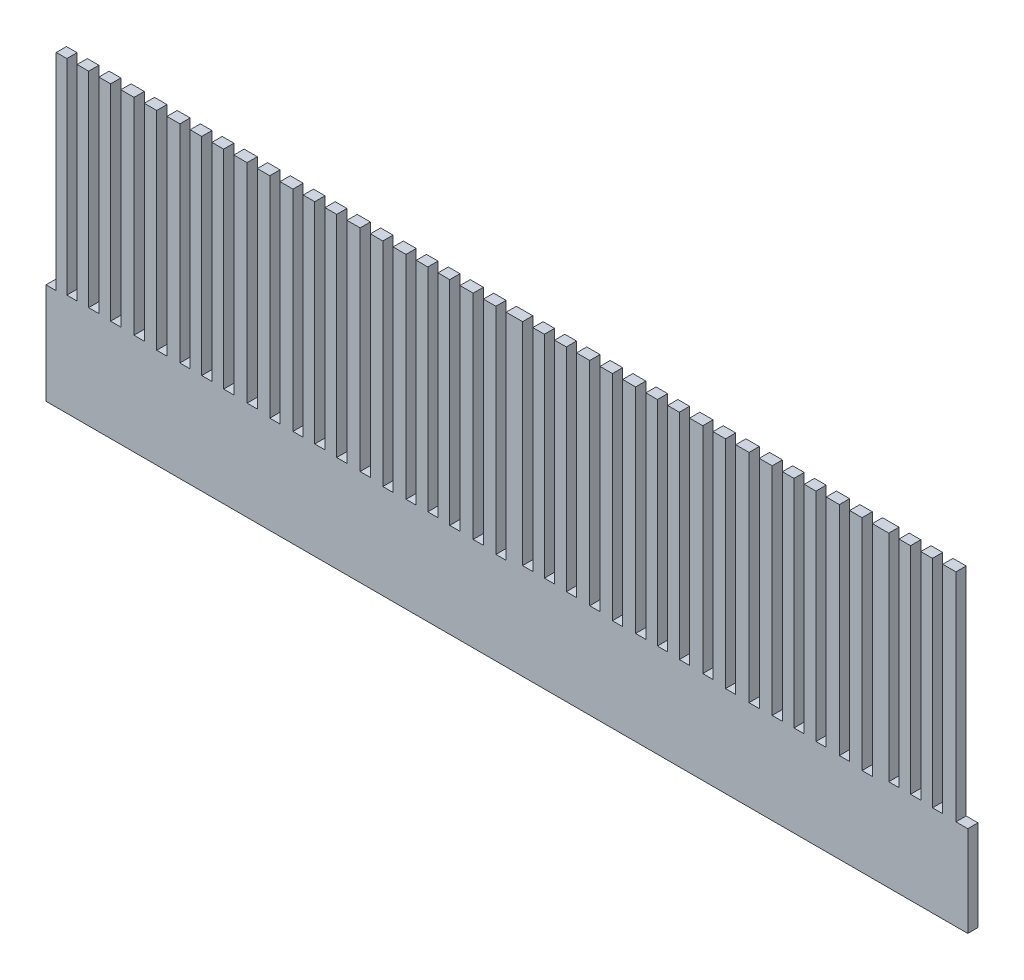
SolidWorks part; units mm, degrees
ref_plane "Front Plane" through (0, 0, 0) normal (0, 0, 1) x (1, 0, 0)
ref_plane "Top Plane" through (0, 0, 0) normal (0, 1, 0) x (1, 0, 0)
ref_plane "Right Plane" through (0, 0, 0) normal (1, 0, 0) x (0, 0, -1)
sketch "Sketch1" plane through (0, 0, 0) normal (0, 0, 1) x (1, 0, 0)
  line L1 (-53.9193, 0) -> (-8.9193, 0)
  line L2 (-53.9193, 0) -> (-53.9193, 15)
  line L3 (-53.9193, 15) -> (-8.9193, 15)
  line L4 (-8.9193, 0) -> (-8.9193, 15)
extrude "Boss-Extrude1" add sketch "Sketch1" along normal blind 0.5
sketch "Sketch2" plane through (0, 0, 0.5) normal (0, 0, 1) x (1, 0, 0)
  line L0 (-52.9014, 16.9986) -> (-52.4014, 16.9986)
  line L1 (-53.9193, 15) -> (-53.4193, 15)
  line L2 (-53.9193, 15) -> (-53.9193, 4.9255)
  line L3 (-53.9193, 4.9255) -> (-53.4193, 4.9255)
  line L4 (-53.4193, 15) -> (-53.4193, 4.9255)
  line L5 (-52.9014, 16.9986) -> (-52.9014, 4.9986)
  line L6 (-52.9014, 4.9986) -> (-52.4014, 4.9986)
  line L7 (-52.4014, 16.9986) -> (-52.4014, 4.9986)
  line L8 (-51.8373, 17.0003) -> (-51.3373, 17.0003)
  line L9 (-51.8373, 17.0003) -> (-51.8373, 5.0003)
  line L10 (-51.8373, 5.0003) -> (-51.3373, 5.0003)
  line L11 (-51.3373, 17.0003) -> (-51.3373, 5.0003)
  line L12 (-50.766, 16.9637) -> (-50.266, 16.9637)
  line L13 (-50.766, 16.9637) -> (-50.766, 4.9637)
  line L14 (-50.766, 4.9637) -> (-50.266, 4.9637)
  line L15 (-50.266, 16.9637) -> (-50.266, 4.9637)
  line L16 (-49.6216, 16.9419) -> (-49.1216, 16.9419)
  line L17 (-49.6216, 16.9419) -> (-49.6216, 4.9419)
  line L18 (-49.6216, 4.9419) -> (-49.1216, 4.9419)
  line L19 (-49.1216, 16.9419) -> (-49.1216, 4.9419)
  line L20 (-48.5139, 16.8613) -> (-48.0139, 16.8613)
  line L21 (-48.5139, 16.8613) -> (-48.5139, 4.8613)
  line L22 (-48.5139, 4.8613) -> (-48.0139, 4.8613)
  line L23 (-48.0139, 16.8613) -> (-48.0139, 4.8613)
  line L24 (-47.3825, 16.888) -> (-46.8825, 16.888)
  line L25 (-47.3825, 16.888) -> (-47.3825, 4.888)
  line L26 (-47.3825, 4.888) -> (-46.8825, 4.888)
  line L27 (-46.8825, 16.888) -> (-46.8825, 4.888)
  line L28 (-46.3184, 16.8897) -> (-45.8184, 16.8897)
  line L29 (-46.3184, 16.8897) -> (-46.3184, 4.8897)
  line L30 (-46.3184, 4.8897) -> (-45.8184, 4.8897)
  line L31 (-45.8184, 16.8897) -> (-45.8184, 4.8897)
  line L32 (-45.2472, 16.8531) -> (-44.7472, 16.8531)
  line L33 (-45.2472, 16.8531) -> (-45.2472, 4.8531)
  line L34 (-45.2472, 4.8531) -> (-44.7472, 4.8531)
  line L35 (-44.7472, 16.8531) -> (-44.7472, 4.8531)
  line L36 (-44.1027, 16.8313) -> (-43.6027, 16.8313)
  line L37 (-44.1027, 16.8313) -> (-44.1027, 4.8313)
  line L38 (-44.1027, 4.8313) -> (-43.6027, 4.8313)
  line L39 (-43.6027, 16.8313) -> (-43.6027, 4.8313)
  line L40 (-42.995, 16.7507) -> (-42.495, 16.7507)
  line L41 (-42.995, 16.7507) -> (-42.995, 4.7507)
  line L42 (-42.995, 4.7507) -> (-42.495, 4.7507)
  line L43 (-42.495, 16.7507) -> (-42.495, 4.7507)
  line L44 (-41.863, 16.7552) -> (-41.363, 16.7552)
  line L45 (-41.863, 16.7552) -> (-41.863, 4.7552)
  line L46 (-41.863, 4.7552) -> (-41.363, 4.7552)
  line L47 (-41.363, 16.7552) -> (-41.363, 4.7552)
  line L48 (-40.799, 16.7569) -> (-40.299, 16.7569)
  line L49 (-40.799, 16.7569) -> (-40.799, 4.7569)
  line L50 (-40.799, 4.7569) -> (-40.299, 4.7569)
  line L51 (-40.299, 16.7569) -> (-40.299, 4.7569)
  line L52 (-39.7277, 16.7203) -> (-39.2277, 16.7203)
  line L53 (-39.7277, 16.7203) -> (-39.7277, 4.7203)
  line L54 (-39.7277, 4.7203) -> (-39.2277, 4.7203)
  line L55 (-39.2277, 16.7203) -> (-39.2277, 4.7203)
  line L56 (-38.5832, 16.6985) -> (-38.0832, 16.6985)
  line L57 (-38.5832, 16.6985) -> (-38.5832, 4.6985)
  line L58 (-38.5832, 4.6985) -> (-38.0832, 4.6985)
  line L59 (-38.0832, 16.6985) -> (-38.0832, 4.6985)
  line L60 (-37.4756, 16.6179) -> (-36.9756, 16.6179)
  line L61 (-37.4756, 16.6179) -> (-37.4756, 4.6179)
  line L62 (-37.4756, 4.6179) -> (-36.9756, 4.6179)
  line L63 (-36.9756, 16.6179) -> (-36.9756, 4.6179)
  line L64 (-36.3442, 16.6446) -> (-35.8442, 16.6446)
  line L65 (-36.3442, 16.6446) -> (-36.3442, 4.6446)
  line L66 (-36.3442, 4.6446) -> (-35.8442, 4.6446)
  line L67 (-35.8442, 16.6446) -> (-35.8442, 4.6446)
  line L68 (-35.2801, 16.6463) -> (-34.7801, 16.6463)
  line L69 (-35.2801, 16.6463) -> (-35.2801, 4.6463)
  line L70 (-35.2801, 4.6463) -> (-34.7801, 4.6463)
  line L71 (-34.7801, 16.6463) -> (-34.7801, 4.6463)
  line L72 (-34.2088, 16.6097) -> (-33.7088, 16.6097)
  line L73 (-34.2088, 16.6097) -> (-34.2088, 4.6097)
  line L74 (-34.2088, 4.6097) -> (-33.7088, 4.6097)
  line L75 (-33.7088, 16.6097) -> (-33.7088, 4.6097)
  line L76 (-33.0644, 16.5879) -> (-32.5644, 16.5879)
  line L77 (-33.0644, 16.5879) -> (-33.0644, 4.5879)
  line L78 (-33.0644, 4.5879) -> (-32.5644, 4.5879)
  line L79 (-32.5644, 16.5879) -> (-32.5644, 4.5879)
  line L80 (-31.9567, 16.5073) -> (-31.4567, 16.5073)
  line L81 (-31.9567, 16.5073) -> (-31.9567, 4.5073)
  line L82 (-31.9567, 4.5073) -> (-31.4567, 4.5073)
  line L83 (-31.4567, 16.5073) -> (-31.4567, 4.5073)
  line L84 (-30.6538, 16.6863) -> (-30.1538, 16.6863)
  line L85 (-30.6538, 16.6863) -> (-30.6538, 4.6863)
  line L86 (-30.6538, 4.6863) -> (-30.1538, 4.6863)
  line L87 (-30.1538, 16.6863) -> (-30.1538, 4.6863)
  line L88 (-29.5897, 16.6879) -> (-29.0897, 16.6879)
  line L89 (-29.5897, 16.6879) -> (-29.5897, 4.6879)
  line L90 (-29.5897, 4.6879) -> (-29.0897, 4.6879)
  line L91 (-29.0897, 16.6879) -> (-29.0897, 4.6879)
  line L92 (-28.5184, 16.6514) -> (-28.0184, 16.6514)
  line L93 (-28.5184, 16.6514) -> (-28.5184, 4.6514)
  line L94 (-28.5184, 4.6514) -> (-28.0184, 4.6514)
  line L95 (-28.0184, 16.6514) -> (-28.0184, 4.6514)
  line L96 (-27.374, 16.6296) -> (-26.874, 16.6296)
  line L97 (-27.374, 16.6296) -> (-27.374, 4.6296)
  line L98 (-27.374, 4.6296) -> (-26.874, 4.6296)
  line L99 (-26.874, 16.6296) -> (-26.874, 4.6296)
  line L100 (-26.2663, 16.549) -> (-25.7663, 16.549)
  line L101 (-26.2663, 16.549) -> (-26.2663, 4.549)
  line L102 (-26.2663, 4.549) -> (-25.7663, 4.549)
  line L103 (-25.7663, 16.549) -> (-25.7663, 4.549)
  line L104 (-25.1349, 16.5757) -> (-24.6349, 16.5757)
  line L105 (-25.1349, 16.5757) -> (-25.1349, 4.5757)
  line L106 (-25.1349, 4.5757) -> (-24.6349, 4.5757)
  line L107 (-24.6349, 16.5757) -> (-24.6349, 4.5757)
  line L108 (-24.0708, 16.5774) -> (-23.5708, 16.5774)
  line L109 (-24.0708, 16.5774) -> (-24.0708, 4.5774)
  line L110 (-24.0708, 4.5774) -> (-23.5708, 4.5774)
  line L111 (-23.5708, 16.5774) -> (-23.5708, 4.5774)
  line L112 (-22.9996, 16.5408) -> (-22.4996, 16.5408)
  line L113 (-22.9996, 16.5408) -> (-22.9996, 4.5408)
  line L114 (-22.9996, 4.5408) -> (-22.4996, 4.5408)
  line L115 (-22.4996, 16.5408) -> (-22.4996, 4.5408)
  line L116 (-21.8551, 16.519) -> (-21.3551, 16.519)
  line L117 (-21.8551, 16.519) -> (-21.8551, 4.519)
  line L118 (-21.8551, 4.519) -> (-21.3551, 4.519)
  line L119 (-21.3551, 16.519) -> (-21.3551, 4.519)
  line L120 (-20.7474, 16.4384) -> (-20.2474, 16.4384)
  line L121 (-20.7474, 16.4384) -> (-20.7474, 4.4384)
  line L122 (-20.7474, 4.4384) -> (-20.2474, 4.4384)
  line L123 (-20.2474, 16.4384) -> (-20.2474, 4.4384)
  line L127 (-19.5979, 16.4185) -> (-19.0979, 16.4185)
  line L128 (-19.5979, 16.4185) -> (-19.5979, 4.4185)
  line L129 (-19.5979, 4.4185) -> (-19.0979, 4.4185)
  line L130 (-19.0979, 16.4185) -> (-19.0979, 4.4185)
  line L131 (-18.4665, 16.4452) -> (-17.9665, 16.4452)
  line L132 (-18.4665, 16.4452) -> (-18.4665, 4.4452)
  line L133 (-18.4665, 4.4452) -> (-17.9665, 4.4452)
  line L134 (-17.9665, 16.4452) -> (-17.9665, 4.4452)
  line L135 (-17.4024, 16.4469) -> (-16.9024, 16.4469)
  line L136 (-17.4024, 16.4469) -> (-17.4024, 4.4469)
  line L137 (-17.4024, 4.4469) -> (-16.9024, 4.4469)
  line L138 (-16.9024, 16.4469) -> (-16.9024, 4.4469)
  line L139 (-16.3312, 16.4104) -> (-15.8312, 16.4104)
  line L140 (-16.3312, 16.4104) -> (-16.3312, 4.4104)
  line L141 (-16.3312, 4.4104) -> (-15.8312, 4.4104)
  line L142 (-15.8312, 16.4104) -> (-15.8312, 4.4104)
  line L143 (-15.1867, 16.3885) -> (-14.6867, 16.3885)
  line L144 (-15.1867, 16.3885) -> (-15.1867, 4.3885)
  line L145 (-15.1867, 4.3885) -> (-14.6867, 4.3885)
  line L146 (-14.6867, 16.3885) -> (-14.6867, 4.3885)
  line L147 (-14.079, 16.308) -> (-13.579, 16.308)
  line L148 (-14.079, 16.308) -> (-14.079, 4.308)
  line L149 (-14.079, 4.308) -> (-13.579, 4.308)
  line L150 (-13.579, 16.308) -> (-13.579, 4.308)
  line L151 (-12.7761, 16.4869) -> (-12.2761, 16.4869)
  line L152 (-12.7761, 16.4869) -> (-12.7761, 4.4869)
  line L153 (-12.7761, 4.4869) -> (-12.2761, 4.4869)
  line L154 (-12.2761, 16.4869) -> (-12.2761, 4.4869)
  line L155 (-11.712, 16.4886) -> (-11.212, 16.4886)
  line L156 (-11.712, 16.4886) -> (-11.712, 4.4886)
  line L157 (-11.712, 4.4886) -> (-11.212, 4.4886)
  line L158 (-11.212, 16.4886) -> (-11.212, 4.4886)
  line L159 (-10.6408, 16.452) -> (-10.1408, 16.452)
  line L160 (-10.6408, 16.452) -> (-10.6408, 4.452)
  line L161 (-10.6408, 4.452) -> (-10.1408, 4.452)
  line L162 (-10.1408, 16.452) -> (-10.1408, 4.452)
  line L163 (-9.4963, 16.4302) -> (-8.6841, 16.4302)
  line L164 (-9.4963, 16.4302) -> (-9.4963, 4.4302)
  line L165 (-9.4963, 4.4302) -> (-8.6841, 4.4302)
  line L166 (-8.6841, 16.4302) -> (-8.6841, 4.4302)
  line L167 (-8.3886, 16.3496) -> (-7.8886, 16.3496)
  line L168 (-8.3886, 16.3496) -> (-8.3886, 4.3496)
  line L169 (-8.3886, 4.3496) -> (-7.8886, 4.3496)
  line L170 (-7.8886, 16.3496) -> (-7.8886, 4.3496)
  line L171 (-7.2572, 16.3763) -> (-6.7572, 16.3763)
  line L172 (-7.2572, 16.3763) -> (-7.2572, 4.3763)
  line L173 (-7.2572, 4.3763) -> (-6.7572, 4.3763)
  line L174 (-6.7572, 16.3763) -> (-6.7572, 4.3763)
  line L175 (-6.1932, 16.378) -> (-5.6932, 16.378)
  line L176 (-6.1932, 16.378) -> (-6.1932, 4.378)
  line L177 (-6.1932, 4.378) -> (-5.6932, 4.378)
  line L178 (-5.6932, 16.378) -> (-5.6932, 4.378)
  line L179 (-5.1219, 16.3415) -> (-4.6219, 16.3415)
  line L180 (-5.1219, 16.3415) -> (-5.1219, 4.3415)
  line L181 (-5.1219, 4.3415) -> (-4.6219, 4.3415)
  line L182 (-4.6219, 16.3415) -> (-4.6219, 4.3415)
  line L183 (-3.9775, 16.3196) -> (-3.4775, 16.3196)
  line L184 (-3.9775, 16.3196) -> (-3.9775, 4.3196)
  line L185 (-3.9775, 4.3196) -> (-3.4775, 4.3196)
  line L186 (-3.4775, 16.3196) -> (-3.4775, 4.3196)
  line L187 (-2.8698, 16.2391) -> (-2.3698, 16.2391)
  line L188 (-2.8698, 16.2391) -> (-2.8698, 4.2391)
  line L189 (-2.8698, 4.2391) -> (-2.3698, 4.2391)
  line L190 (-2.3698, 16.2391) -> (-2.3698, 4.2391)
extrude "Cut-Extrude1" cut sketch "Sketch2" against normal blind 0.5
